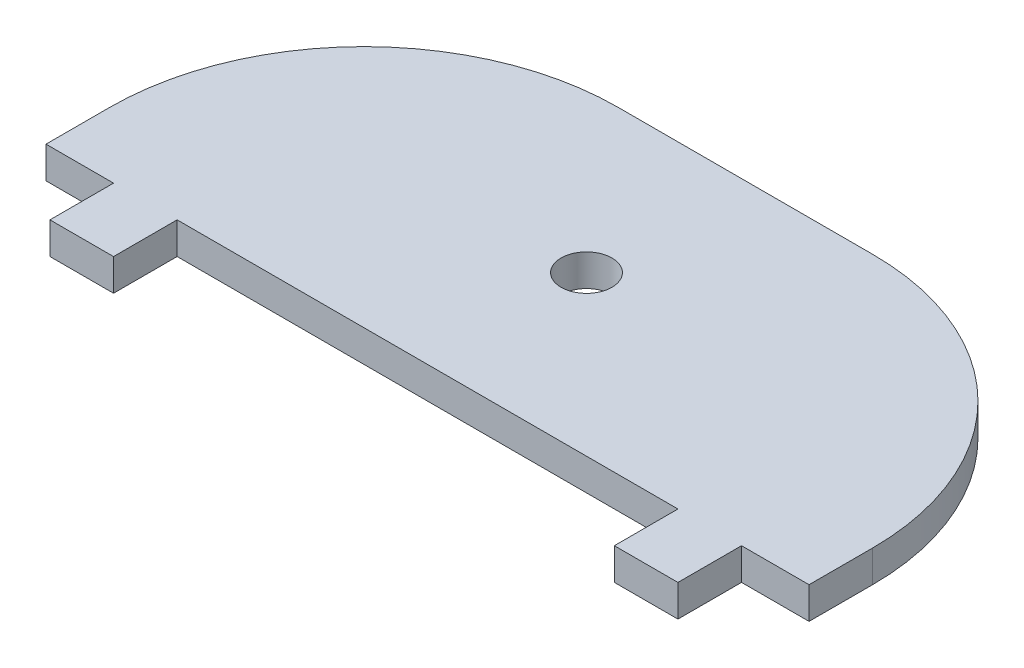
SolidWorks part; units mm, degrees
material "Maple"
ref_plane "Front Plane" through (0, 0, 0) normal (0, 0, 1) x (1, 0, 0)
ref_plane "Top Plane" through (0, 0, 0) normal (0, 1, 0) x (1, 0, 0)
ref_plane "Right Plane" through (0, 0, 0) normal (1, 0, 0) x (0, 0, -1)
sketch "Sketch1" plane through (0, 0, 0) normal (0, 1, 0) x (1, 0, 0)
  line L0 (0, 5.9579) -> (0, -5.7243) construction
  line L1 (30, -12.5) -> (-30, -12.5) construction
  line L2 (30, -12.5) -> (30, 12.5)
  line L3 (30, 12.5) -> (-30, 12.5)
  line L4 (-30, -12.5) -> (-30, 12.5)
  line L5 (30, -12.5) -> (-30, 12.5) construction
  line L6 (30, 12.5) -> (-30, -12.5) construction
  line L7 (24.69, -12.5) -> (24.69, -17.5)
  line L8 (-24.69, -12.5) -> (-19.69, -12.5) construction
  line L9 (-24.69, -12.5) -> (-24.69, -17.5)
  line L10 (-24.69, -17.5) -> (-19.69, -17.5)
  line L11 (-19.69, -12.5) -> (-19.69, -17.5)
  line L12 (24.69, -17.5) -> (19.69, -17.5)
  line L13 (19.69, -12.5) -> (19.69, -17.5)
  line L14 (-30, -12.5) -> (-24.69, -12.5)
  line L15 (-19.69, -12.5) -> (19.69, -12.5)
  line L16 (24.69, -12.5) -> (30, -12.5)
  circle A0 centre (0, 0) radius 2
  point P0 (0, 0)
  dimension "D6" = 4
  dimension "D1" = 25
  dimension "D2" = 60
  dimension "D3" = 5
  dimension "D4" = 5
  dimension "D5" = 39.38
  dimension "D7" = 12.5
extrude "Boss-Extrude1" add sketch "Sketch1" along normal mid plane 2.5
fillet "Fillet1" radius 20 2 edges at (30, 0, -12.5) (-30, 0, -12.5)
